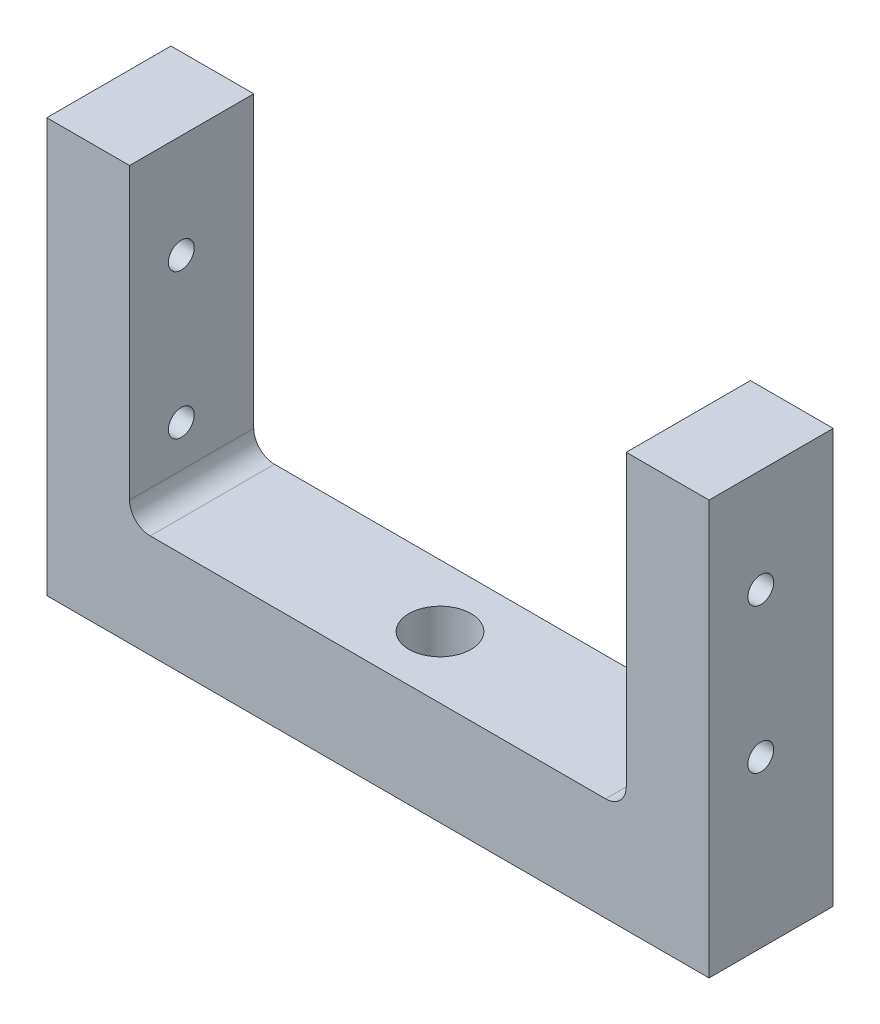
SolidWorks part; units mm, degrees
ref_plane "Plan de face" through (0, 0, 0) normal (0, 0, 1) x (1, 0, 0)
ref_plane "Plan de dessus" through (0, 0, 0) normal (0, 1, 0) x (1, 0, 0)
ref_plane "Plan de droite" through (0, 0, 0) normal (1, 0, 0) x (0, 0, -1)
sketch "Esquisse1" plane through (0, 0, 0) normal (0, 0, 1) x (1, 0, 0)
  line L0 (-16, 10) -> (-12, 10) construction
  line L1 (-16, 10) -> (16, 10)
  line L2 (-16, 10) -> (-16, -10)
  line L3 (-16, -10) -> (16, -10)
  line L4 (16, 10) -> (16, -10)
  line L6 (-12, 10) -> (12, 10)
  line L7 (-12, 10) -> (-12, -5)
  line L8 (-12, -5) -> (12, -5)
  line L9 (12, 10) -> (12, -5)
  dimension "D1" = 32
  dimension "D2" = 20
  dimension "D3" = 16
  dimension "D4" = 10
  dimension "D5" = 4
  dimension "D6" = 24
  dimension "D7" = 15
extrude "Boss.-Extru.1" add sketch "Esquisse1" along normal blind 6 contours L1 L9 L8 L7 L2 L3 L4
sketch "Esquisse2" plane through (0, -5, 0) normal (0, 1, 0) x (1, 0, 0)
  line L0 (-12, -6) -> (0, -6) construction
  line L1 (-12, -6) -> (12, -6) construction
  line L2 (0, -6) -> (0, 0) construction
  circle A0 centre (0, -3) radius 1.5
  dimension "D1" = 3
extrude "Enlèv. mat.-Extru.1" cut sketch "Esquisse2" against normal blind 5 contours A0
sketch "Esquisse3" plane through (16, 0, 0) normal (1, 0, 0) x (0, 0, -1)
  line L0 (-6, 10) -> (-6, 5)
  line L1 (-6, 10) -> (-6, -10) construction
  line L2 (-6, 10) -> (-6, -2)
  line L4 (-6, 5) -> (0, 5) construction
  line L5 (0, 10) -> (0, -10) construction
  line L6 (-6, -2) -> (0, -2) construction
  circle A2 centre (-3.5, 5) radius 0.625
  circle A3 centre (-3.5, -2) radius 0.625
  dimension "D3" = 2.5
  dimension "D4" = 2.5
  dimension "D5" = 1.25
  dimension "D6" = 1.25
  dimension "D1" = 5
  dimension "D2" = 12
extrude "Enlèv. mat.-Extru.2" cut sketch "Esquisse3" against normal through all contours A2 | A3
fillet "Congé2" radius 1 1 edges at (-12, -5, 3)
fillet "Congé3" radius 1 1 edges at (12, -5, 3)
